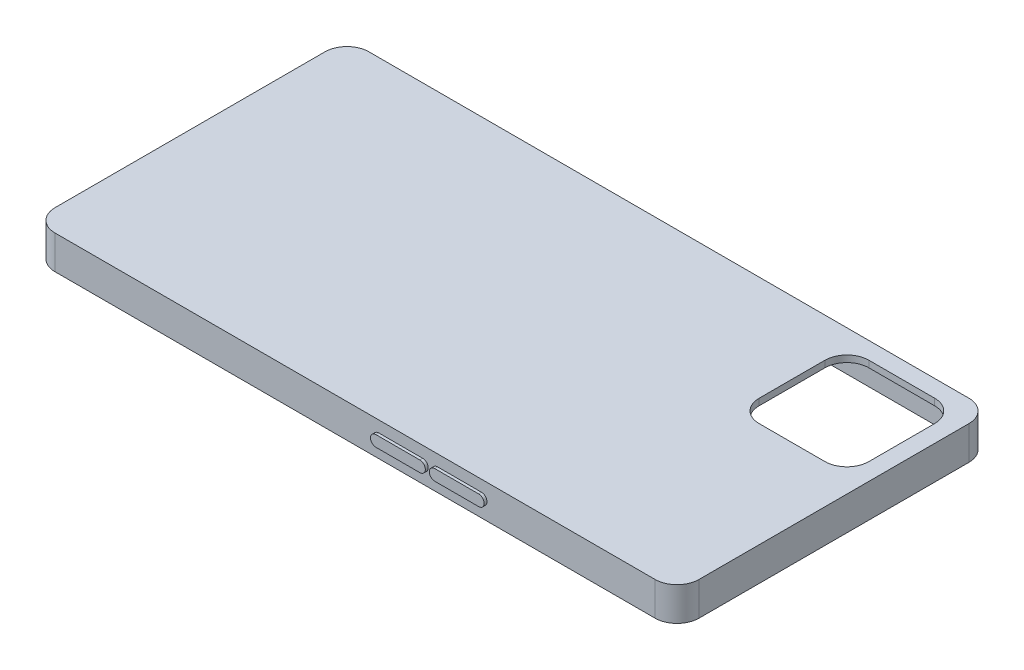
SolidWorks part; units mm, degrees
material "ABS PC"
ref_plane "Front Plane" through (0, 0, 0) normal (0, 0, 1) x (1, 0, 0)
ref_plane "Top Plane" through (0, 0, 0) normal (0, 1, 0) x (1, 0, 0)
ref_plane "Right Plane" through (0, 0, 0) normal (1, 0, 0) x (0, 0, -1)
sketch "Sketch1" plane through (0, 0, 0) normal (0, 1, 0) x (1, 0, 0)
  line L1 (-73.35, 35.75) -> (73.35, 35.75)
  line L2 (-73.35, 35.75) -> (-73.35, -35.75)
  line L3 (-73.35, -35.75) -> (73.35, -35.75)
  line L4 (73.35, 35.75) -> (73.35, -35.75)
  line L5 (-73.35, 35.75) -> (73.35, -35.75) construction
  line L6 (-73.35, -35.75) -> (73.35, 35.75) construction
  point P0 (0, 0)
  dimension "D1" = 146.7
  dimension "D2" = 71.5
extrude "Base" add sketch "Sketch1" along normal blind 7.65
fillet "Curves case" radius 5 4 edges at (-73.35, 3.825, -35.75) (-73.35, 3.825, 35.75) (73.35, 3.825, 35.75) (73.35, 3.825, -35.75)
shell "Shell" thickness 1.5
sketch "Sketch2" plane through (0, 7.65, 0) normal (0, 1, 0) x (1, 0, 0)
  line L0 (68.35, 35.75) -> (-68.35, 35.75) construction
  line L1 (44.4457, 31.85) -> (69.4457, 31.85)
  line L2 (44.4457, 31.85) -> (44.4457, 6.85)
  line L3 (44.4457, 6.85) -> (69.4457, 6.85)
  line L4 (69.4457, 31.85) -> (69.4457, 6.85)
  line L5 (44.4457, 31.85) -> (69.4457, 6.85) construction
  line L6 (44.4457, 6.85) -> (69.4457, 31.85) construction
  line L7 (73.35, -30.75) -> (73.35, 30.75) construction
  point P0 (56.9457, 19.35)
  dimension "D1" = 25
  dimension "D2" = 3.9
  dimension "D3" = 3.9043
  dimension "D4" = 25
extrude "Camera Hole" cut sketch "Sketch2" against normal through all and the other way through all
fillet "Curves Camera" radius 5 4 edges at (44.4457, 6.9, -6.85) (69.4457, 6.9, -6.85) (69.4457, 6.9, -31.85) (44.4457, 6.9, -31.85)
sketch "Sketch6" plane through (-73.35, 0, 0) normal (-1, 0, 0) x (0, 0, 1)
  line L0 (-2.425, 3.0603) -> (2.425, 3.0603) construction
  line L1 (-2.425, 4.7227) -> (2.425, 4.7227)
  line L2 (-2.425, 1.3979) -> (2.425, 1.3979)
  line L5 (-30.75, 7.65) -> (-30.75, 0) construction
  line L6 (30.75, 0) -> (30.75, 7.65) construction
  arc A0 (-2.425, 4.7227) -> (-2.425, 1.3979) centre (-2.425, 3.0603) ccw
  arc A1 (2.425, 1.3979) -> (2.425, 4.7227) centre (2.425, 3.0603) ccw
  point P2 (0, 3.0603)
  dimension "D2" = 28.325
  dimension "D3" = 4.85
  dimension "D1" = 28.325
  dimension "D4" = 61.5
extrude "Charger bottom" cut sketch "Sketch6" against normal blind 9.65 and the other way through all
sketch "Sketch9" plane through (0, 0, 35.75) normal (0, 0, 1) x (1, 0, 0)
  line L0 (5.4071, 3.825) -> (15.4071, 3.825) construction
  line L1 (5.4071, 5.075) -> (15.4071, 5.075)
  line L2 (5.4071, 2.575) -> (15.4071, 2.575)
  line L3 (18.8039, 3.825) -> (28.8039, 3.825) construction
  line L6 (18.8039, 5.075) -> (28.8039, 5.075)
  line L9 (18.8039, 2.575) -> (28.8039, 2.575)
  line L10 (-68.35, 7.65) -> (68.35, 7.65) construction
  line L11 (-68.35, 0) -> (68.35, 0) construction
  arc A0 (5.4071, 5.075) -> (5.4071, 2.575) centre (5.4071, 3.825) ccw
  arc A1 (15.4071, 2.575) -> (15.4071, 5.075) centre (15.4071, 3.825) ccw
  arc A10 (18.8039, 5.075) -> (18.8039, 2.575) centre (18.8039, 3.825) ccw
  arc A11 (28.8039, 2.575) -> (28.8039, 5.075) centre (28.8039, 3.825) ccw
  point P2 (10.4071, 3.825)
  point P9 (23.8039, 3.825)
  point P35 (5.4071, 3.951)
  point P36 (0, 0)
  dimension "D1" = 10
  dimension "D2" = 10
  dimension "D3" = 2.575
  dimension "D4" = 7.65
  dimension "D5" = 2.5
  dimension "D6" = 2.575
  dimension "D7" = 2.575
  dimension "D8" = 2.575
extrude "Volume Bottom" add sketch "Sketch9" along normal blind 0.65
sketch "Sketch11" plane through (0, 0, -35.75) normal (0, 0, -1) x (-1, 0, 0)
  line L0 (-20.9946, 3.825) -> (-6.5048, 3.825) construction
  line L1 (-20.9946, 5.075) -> (-6.5048, 5.075)
  line L2 (-20.9946, 2.575) -> (-6.5048, 2.575)
  line L3 (-68.35, 7.65) -> (68.35, 7.65) construction
  line L4 (-68.35, 0) -> (68.35, 0) construction
  arc A0 (-20.9946, 5.075) -> (-20.9946, 2.575) centre (-20.9946, 3.825) ccw
  arc A1 (-6.5048, 2.575) -> (-6.5048, 5.075) centre (-6.5048, 3.825) ccw
  point P2 (-13.7497, 3.825)
  dimension "D1" = 2.575
  dimension "D2" = 2.575
extrude "Turn on/off" add sketch "Sketch11" along normal blind 0.65
